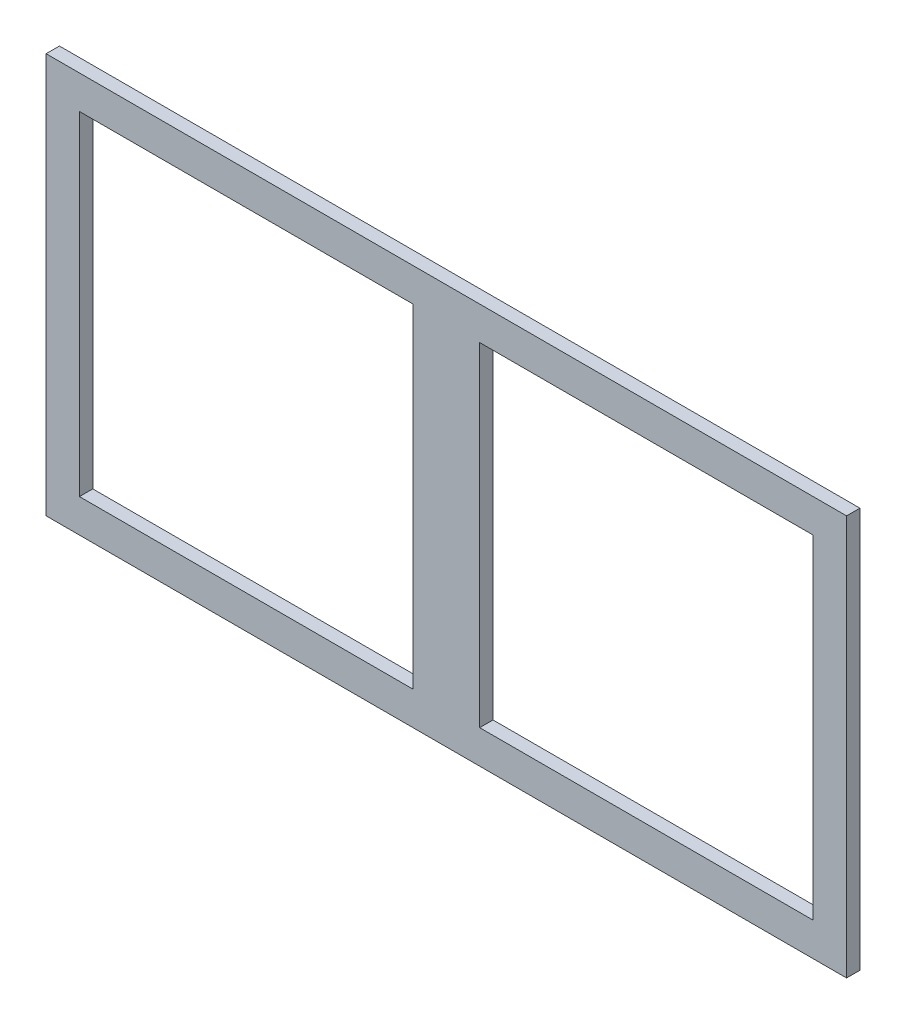
SolidWorks part; units mm, degrees
ref_plane "Ebene vorne" through (0, 0, 0) normal (0, 0, 1) x (1, 0, 0)
ref_plane "Ebene oben" through (0, 0, 0) normal (0, 1, 0) x (1, 0, 0)
ref_plane "Ebene rechts" through (0, 0, 0) normal (1, 0, 0) x (0, 0, -1)
sketch "Skizze1" plane through (0, 0, 0) normal (0, 0, 1) x (1, 0, 0)
  line L0 (150, 0) -> (-150, 0)
  line L1 (-150, 0) -> (-150, 150)
  line L2 (-150, 150) -> (150, 150)
  line L4 (0, 0) -> (0, 197.9645) construction
  line L6 (150, 0) -> (150, 150)
  point P11 (0, 150)
  dimension "D1" = 300
  dimension "150" = 150
extrude "Aufsatz-Linear austragen1" add sketch "Skizze1" along normal blind 5
sketch "Skizze3" plane through (0, 0, 5) normal (0, 0, 1) x (1, 0, 0)
  line L0 (-150, 0) -> (150, 0) construction
  line L1 (-137.5, 137.5) -> (-12.5, 137.5)
  line L2 (-137.5, 137.5) -> (-137.5, 12.5)
  line L3 (-137.5, 12.5) -> (-12.5, 12.5)
  line L4 (-12.5, 137.5) -> (-12.5, 12.5)
  line L5 (0, 0) -> (0, 150) construction
  line L6 (-150, 75) -> (-144.9482, 75) construction
  line L7 (-150, 150) -> (-150, 0) construction
  line L8 (-137.5, 75) -> (-132.4482, 75) construction
  line L9 (150, 150) -> (-150, 150) construction
  line L10 (137.5, 75) -> (132.4482, 75) construction
  line L11 (150, 75) -> (144.9482, 75) construction
  line L12 (12.5, 137.5) -> (12.5, 12.5)
  line L13 (137.5, 12.5) -> (12.5, 12.5)
  line L14 (137.5, 137.5) -> (137.5, 12.5)
  line L15 (137.5, 137.5) -> (12.5, 137.5)
  dimension "D1" = 125
  dimension "D2" = 12.5
  dimension "125" = 125
  dimension "D3" = 12.5
extrude "Schnitt-Linear austragen1" cut sketch "Skizze3" against normal through all
